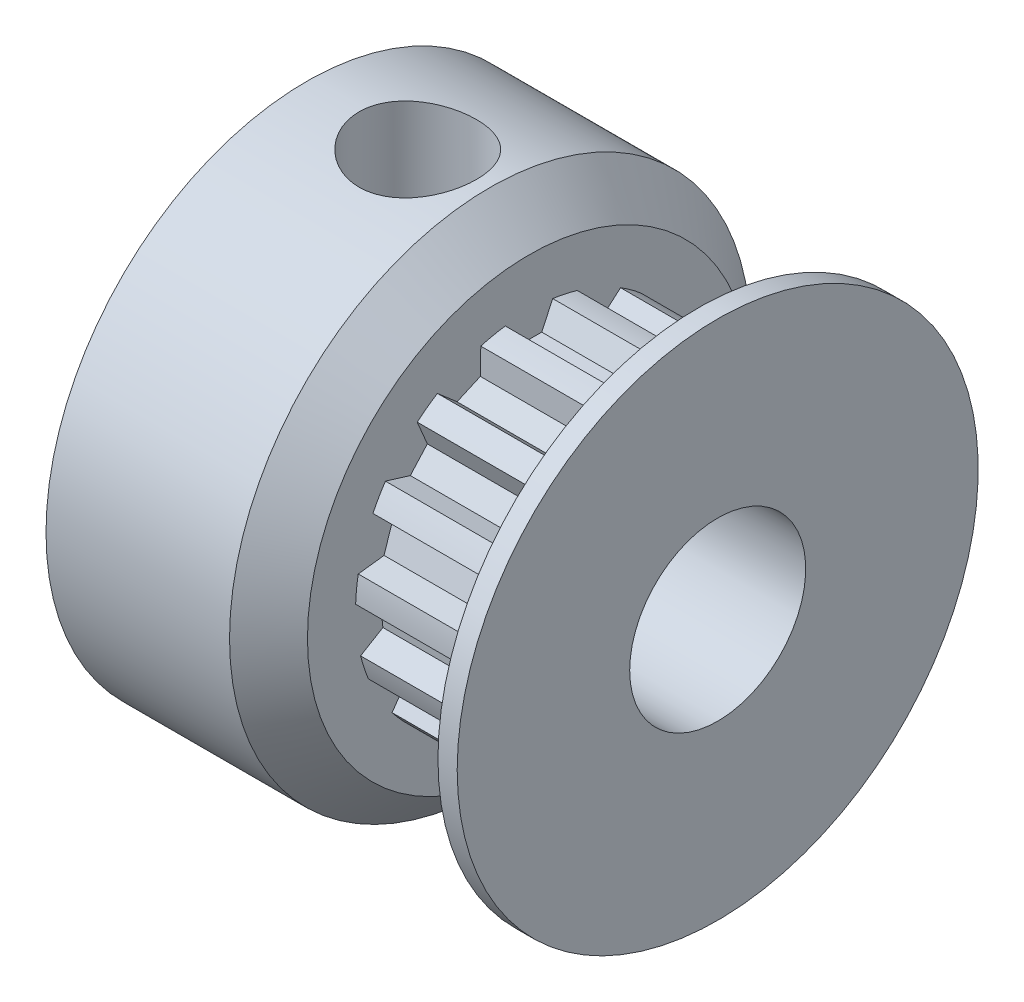
SolidWorks part; units mm, degrees
ref_plane "Front Plane" through (0, 0, 0) normal (0, 0, 1) x (1, 0, 0)
ref_plane "Top Plane" through (0, 0, 0) normal (0, 1, 0) x (1, 0, 0)
ref_plane "Right Plane" through (0, 0, 0) normal (1, 0, 0) x (0, 0, -1)
sketch "Sketch2" plane through (0, 0, 0) normal (1, 0, 0) x (0, 0, -1)
  line L3 (0, 0) -> (0, 4.0259) construction
  line L6 (0, -4.5339) -> (0, -4.8514) construction
  line L7 (-0.5715, 4.4977) -> (-0.3446, 4.0111)
  line L8 (0.5715, 4.4977) -> (0.3446, 4.0111)
  line L9 (-0.5715, 4.4977) -> (-0.6418, 4.6486)
  line L10 (0.5715, 4.4977) -> (0.6418, 4.6486)
  line L12 (-0.3446, 4.0111) -> (0.3446, 4.0111)
  line L14 (0, 4.5339) -> (0, 4.8514) construction
  line L15 (0, 0) -> (0, -1.143) construction
  circle A0 centre (0, 0) radius 4.8514 construction
  circle A1 centre (0, 0) radius 4.0259 construction
  circle A2 centre (0, 0) radius 4.5339 construction
  arc A7 (0.6418, 4.6486) -> (-0.6418, 4.6486) centre (0, 0) ccw
  point P5 (0, 4.6926)
  dimension "D3" = 0.3175
  dimension "D1" = 50
sketch "Sketch1" plane through (0, 0, 0) normal (0, 0, 1) x (1, 0, 0)
  line L0 (-5.5626, 0) -> (5.5626, 0) construction
  line L1 (-5.5626, 2.3813) -> (5.5626, 2.3813)
  line L2 (-5.5626, 2.3813) -> (-5.5626, 7.0485)
  line L3 (-5.5626, 7.0485) -> (-0.5969, 7.0485)
  line L4 (-0.5969, 7.0485) -> (0.4572, 5.9944)
  line L5 (0.4572, 5.9944) -> (0.4572, 4.8514)
  line L6 (0.4572, 4.8514) -> (4.5212, 4.8514)
  line L7 (4.5212, 4.8514) -> (4.5212, 5.4229)
  line L8 (4.5212, 4.8514) -> (5.5626, 4.8514) construction
  line L9 (5.0419, 7.0485) -> (5.5626, 7.0485)
  line L10 (5.5626, 7.0485) -> (5.5626, 2.3813)
  line L11 (5.0419, 4.8514) -> (5.0419, 7.0485) construction
  line L12 (-3.0797, 7.0485) -> (-3.0797, 2.3812) construction
  arc A0 (4.5212, 5.4229) -> (5.0419, 7.0485) centre (7.3191, 5.4229) cw
  dimension "Bore Size" = 4.7625
  dimension "Overall Width" = 11.1252
  dimension "Inside Width" = 4.064
  dimension "Outside Width" = 5.1054
  dimension "Hub Dia" = 14.097
  dimension "OD" = 14.097
  dimension "D1" = 45
  dimension "D2" = 9.7028
  dimension "D3" = 1.143
  dimension "D4" = 0.5715
revolve "Revolve1" add sketch "Sketch1" angle 360 mid plane about L0
sketch "Sketch4" plane through (0.4572, 0, 0) normal (1, 0, 0) x (0, 0, -1)
  circle A0 centre (0, 0) radius 4.6926
  circle A1 centre (0, 0) radius 4.8514 construction
  circle A2 centre (0, 0) radius 4.8514
extrude "Cut-Extrude2" cut sketch "Sketch4" along normal up to surface (4.064 mm away) up to face at (4.5212, 0, 4.8514)
sketch "Sketch3" plane through (0.4572, 0, 0) normal (1, 0, 0) x (0, 0, -1)
  line L2 (-0.5715, 4.4977) -> (-0.3446, 4.0111) construction
  line L3 (-0.3446, 4.0111) -> (0.3446, 4.0111) construction
  line L4 (0.5715, 4.4977) -> (0.3446, 4.0111) construction
  line L5 (-0.6418, 4.6486) -> (-0.3446, 4.0111)
  line L6 (-0.3446, 4.0111) -> (0.3446, 4.0111)
  line L7 (0.6418, 4.6486) -> (0.3446, 4.0111)
  arc A1 (0.6418, 4.6486) -> (-0.6418, 4.6486) centre (0, 0) ccw construction
  arc A2 (0.6418, 4.6486) -> (-0.6418, 4.6486) centre (0, 0) ccw
extrude "Cut-Extrude1" cut sketch "Sketch3" along normal up to surface (4.064 mm away) up to face at (4.5212, 0, 5.4229)
pattern_circular "CirPattern1" count 15 over 360 about axis through (0, 0, 0) along (1, 0, 0) of "Cut-Extrude1"
sketch "Sketch5" plane through (0, 0, 0) normal (0, 0, 1) x (1, 0, 0)
  line L1 (4.5212, 5.4229) -> (4.5212, -5.4229) construction
  point P0 (4.5212, 0)
sketch "Sketch6" plane through (0, 0, 0) normal (0, 1, 0) x (1, 0, 0)
  line L0 (-5.5626, 0) -> (-4.1402, 0) construction
  line L1 (-5.5626, 7.0485) -> (-5.5626, -7.0485) construction
  line L2 (0.4572, 0) -> (-0.9652, 0) construction
  line L3 (0.4572, -0.3446) -> (0.4572, 0.3446) construction
  circle A0 centre (-2.5527, 0) radius 1.5875
  dimension "D1" = 3.175
extrude "Cut-Extrude3" cut sketch "Sketch6" along normal through all
pattern_circular "CirPattern2" [suppressed] count 2 over 90
equation "\"D3@Sketch2\" = (\"hs@Sketch2\"-\"ht@Sketch2\")/2"
equation "\"D2@Sketch1\" = \"PD@Sketch2\""
equation "\"D3@Sketch1\" = \"hs@Sketch2\""
equation "\"D4@Sketch1\" = \"D3@Sketch1\"/2"
